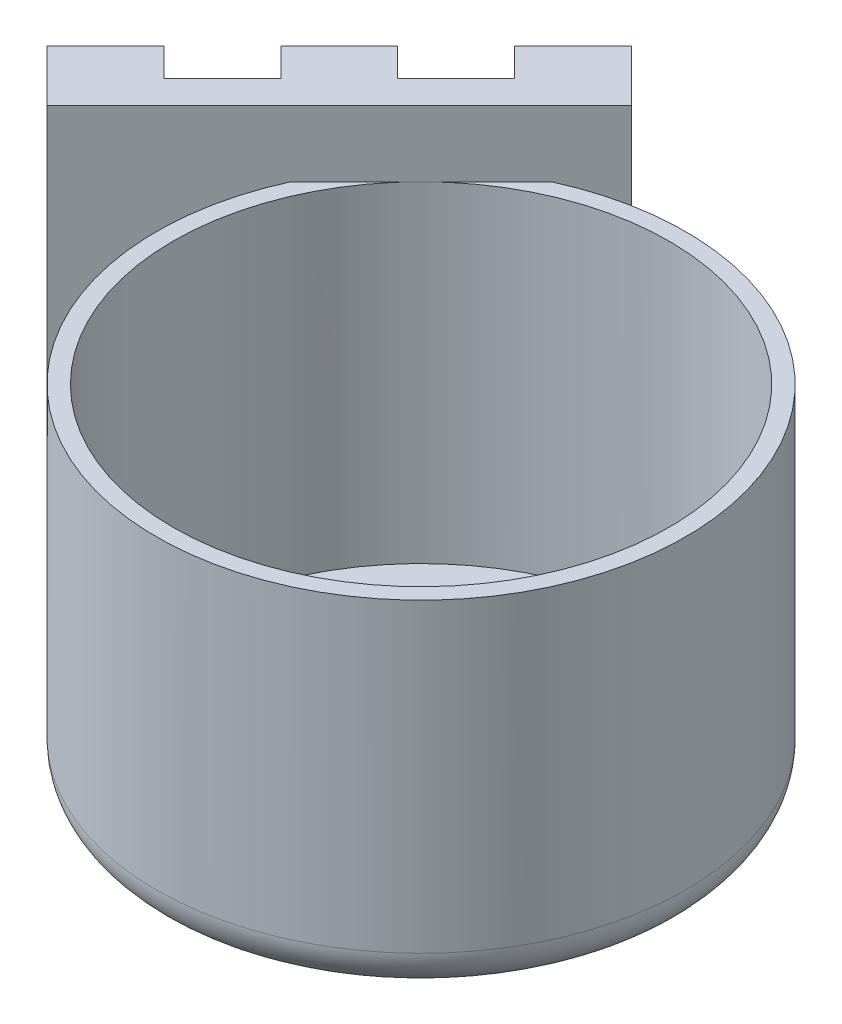
SolidWorks part; units mm, degrees
ref_plane "Front Plane" through (0, 0, 0) normal (0, 0, 1) x (1, 0, 0)
ref_plane "Top Plane" through (0, 0, 0) normal (0, 1, 0) x (1, 0, 0)
ref_plane "Right Plane" through (0, 0, 0) normal (1, 0, 0) x (0, 0, -1)
sketch "Sketch1" plane through (0, 0, 0) normal (0, 1, 0) x (1, 0, 0)
  circle A0 centre (0, 0) radius 40.64
  dimension "D1" = 81.28
extrude "Boss-Extrude1" add sketch "Sketch1" along normal blind 53.34
fillet "Fillet1" radius 6.35 1 edges at (0, 0, 40.64)
sketch "Sketch2" plane through (0, 53.34, 0) normal (0, 1, 0) x (1, 0, 0)
  circle A0 centre (0, 0) radius 38.1
  dimension "D1" = 76.2
extrude "Cut-Extrude1" cut sketch "Sketch2" against normal blind 50.8
ref_plane "Plane1" through (0, 0, 0) normal (-0.7071, 0, 0.7071) x (0.7071, 0, 0.7071)
ref_plane "Plane2" through (-28.7368, 0, 28.7368) normal (-0.7071, 0, 0.7071) x (0.7071, 0, 0.7071)
sketch "Sketch7" plane through (-28.7368, 0, 28.7368) normal (-0.7071, 0, 0.7071) x (0.7071, 0, 0.7071)
  line L0 (40.64, 6.35) -> (40.64, 53.34) construction
  line L1 (-38.1, 63.5) -> (-43.18, 63.5)
  line L2 (-38.1, 63.5) -> (-38.1, 6.35)
  line L3 (-38.1, 6.35) -> (-43.18, 6.35)
  line L4 (-43.18, 63.5) -> (-43.18, 6.35)
  line L5 (-34.29, 0) -> (34.29, 0) construction
  dimension "D1" = 57.15
  dimension "D2" = 78.74
  dimension "D3" = 5.08
  dimension "D4" = 6.35
extrude "Boss-Extrude3" add sketch "Sketch7" against normal blind 63.5 separate body
sketch "Sketch8" plane through (-30.5329, 0, -30.5329) normal (-0.7071, 0, -0.7071) x (-0.7071, 0, 0.7071)
  line L0 (40.64, 63.5) -> (40.64, 6.35) construction
  line L1 (40.64, 63.5) -> (27.94, 63.5)
  line L2 (40.64, 63.5) -> (40.64, 57.15)
  line L3 (40.64, 57.15) -> (27.94, 57.15)
  line L4 (27.94, 63.5) -> (27.94, 57.15)
  line L5 (40.64, 38.1) -> (27.94, 38.1)
  line L6 (40.64, 38.1) -> (40.64, 31.75)
  line L7 (40.64, 31.75) -> (27.94, 31.75)
  line L8 (27.94, 38.1) -> (27.94, 31.75)
  line L9 (15.24, 63.5) -> (15.24, 57.15)
  line L10 (40.64, 12.7) -> (27.94, 12.7)
  line L11 (40.64, 12.7) -> (40.64, 6.35)
  line L12 (40.64, 6.35) -> (27.94, 6.35)
  line L13 (27.94, 12.7) -> (27.94, 6.35)
  line L14 (15.24, 63.5) -> (2.54, 63.5)
  line L15 (2.54, 63.5) -> (2.54, 57.15)
  line L16 (15.24, 57.15) -> (2.54, 57.15)
  line L17 (15.24, 38.1) -> (15.24, 31.75)
  line L18 (15.24, 38.1) -> (2.54, 38.1)
  line L19 (2.54, 38.1) -> (2.54, 31.75)
  line L20 (15.24, 31.75) -> (2.54, 31.75)
  line L21 (15.24, 12.7) -> (15.24, 6.35)
  line L22 (15.24, 12.7) -> (2.54, 12.7)
  line L23 (2.54, 12.7) -> (2.54, 6.35)
  line L24 (15.24, 6.35) -> (2.54, 6.35)
  line L25 (-10.16, 63.5) -> (-10.16, 57.15)
  line L26 (-10.16, 63.5) -> (-22.86, 63.5)
  line L27 (-22.86, 63.5) -> (-22.86, 57.15)
  line L28 (-10.16, 57.15) -> (-22.86, 57.15)
  line L29 (-10.16, 38.1) -> (-10.16, 31.75)
  line L30 (-10.16, 38.1) -> (-22.86, 38.1)
  line L31 (-22.86, 38.1) -> (-22.86, 31.75)
  line L32 (-10.16, 31.75) -> (-22.86, 31.75)
  line L33 (-10.16, 12.7) -> (-10.16, 6.35)
  line L34 (-10.16, 12.7) -> (-22.86, 12.7)
  line L35 (-22.86, 12.7) -> (-22.86, 6.35)
  line L36 (-10.16, 6.35) -> (-22.86, 6.35)
  dimension "D1" = 6.35
  dimension "D2" = 12.7
  dimension "D3" = 12.7
  dimension "D4" = 6.35
  dimension "D5" = 19.05
  dimension "D6" = 6.35
  dimension "D7" = 12.7
  dimension "D8" = 19.05
  dimension "D9" = 3
extrude "Boss-Extrude4" add sketch "Sketch8" along normal blind 6.096
